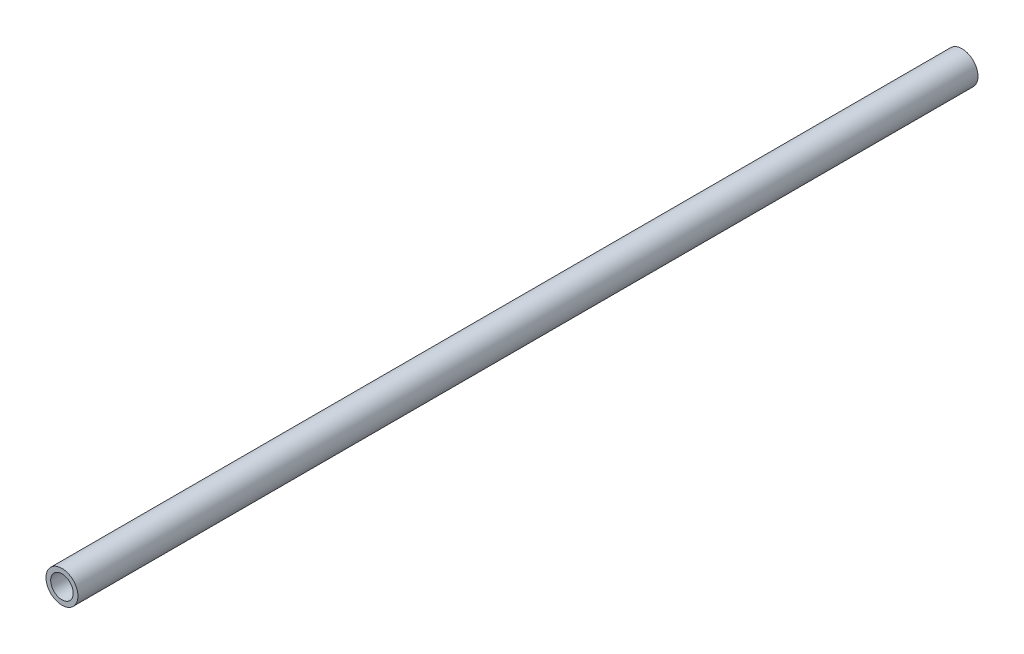
SolidWorks part; units mm, degrees
material "1.4301 (X5CrNi18-10)"
ref_plane "Vorne" through (0, 0, 0) normal (0, 0, 1) x (1, 0, 0)
ref_plane "Oben" through (0, 0, 0) normal (0, 1, 0) x (1, 0, 0)
ref_plane "Rechts" through (0, 0, 0) normal (1, 0, 0) x (0, 0, -1)
sketch "Skizze1" plane through (0, 0, 0) normal (0, 0, 1) x (1, 0, 0)
  circle A0 centre (0, 0) radius 10.65
  circle A1 centre (0, 0) radius 7.5
  dimension "D1" = 21.3
  dimension "D2" = 15
extrude "Linear austragen1" add sketch "Skizze1" along normal blind 600
cosmetic thread "Gewindedarstellung1" parameters "D1"=30, "D2"=18.63
